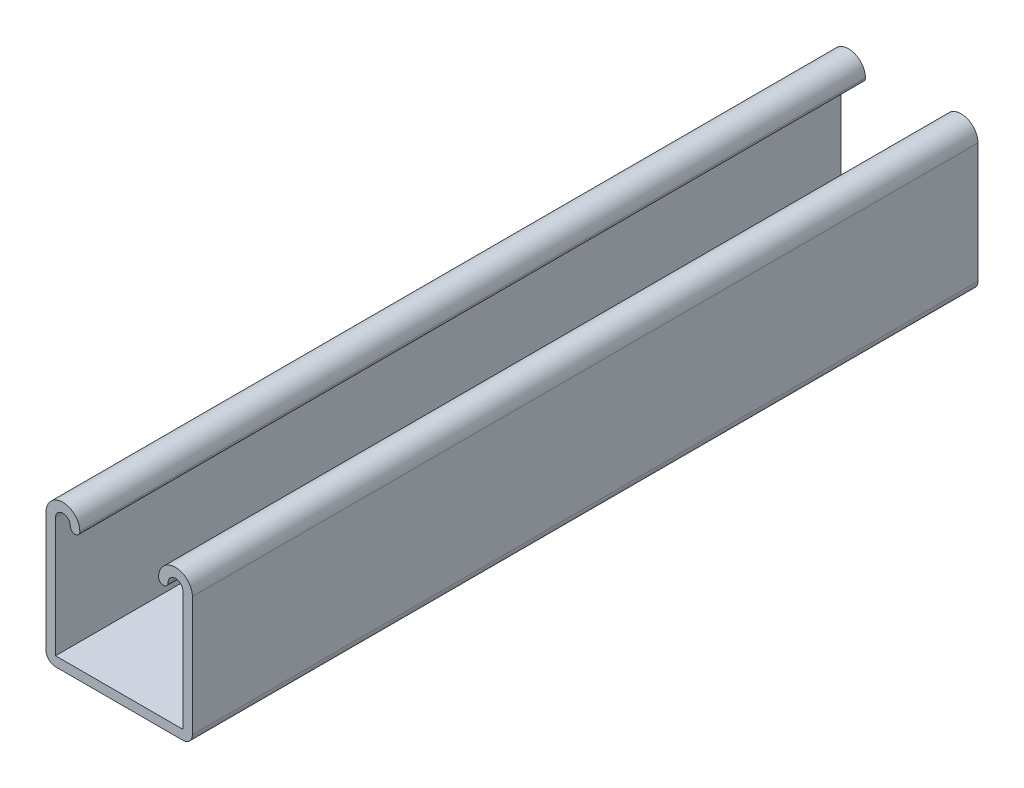
SolidWorks part; units mm, degrees
material "普通碳钢"
ref_plane "前视基准面" through (0, 0, 0) normal (0, 0, 1) x (1, 0, 0)
ref_plane "上视基准面" through (0, 0, 0) normal (0, 1, 0) x (1, 0, 0)
ref_plane "右视基准面" through (0, 0, 0) normal (1, 0, 0) x (0, 0, -1)
sketch "草图1" plane through (0, 0, 0) normal (0, 0, 1) x (1, 0, 0)
  line L0 (0, 0) -> (35.98, 0)
  line L1 (17.99, 2.6924) -> (17.99, -3.3917) construction
  line L2 (35.98, 2.6924) -> (0, 2.6924)
  line L3 (35.98, 19.6088) -> (0, 19.6088) construction
  line L4 (35.98, 2.6924) -> (35.98, 36.5252)
  line L5 (38.6724, 2.6924) -> (38.6724, 36.5252)
  line L6 (-2.6924, 2.6924) -> (-2.6924, 36.5252)
  line L7 (0, 2.6924) -> (0, 36.5252)
  line L8 (17.99, 19.6088) -> (17.99, 2.6924) construction
  arc A0 (35.98, 0) -> (38.6724, 2.6924) centre (35.98, 2.6924) ccw
  arc A1 (35.98, 36.5252) -> (31.8144, 36.5252) centre (33.8972, 36.5252) ccw
  arc A2 (38.6724, 36.5252) -> (29.122, 36.5252) centre (33.8972, 36.5252) ccw
  arc A3 (29.122, 36.5252) -> (31.8144, 36.5252) centre (30.4682, 36.5252) ccw
  arc A4 (6.858, 36.5252) -> (4.1656, 36.5252) centre (5.5118, 36.5252) cw
  arc A5 (-2.6924, 36.5252) -> (6.858, 36.5252) centre (2.0828, 36.5252) cw
  arc A6 (0, 36.5252) -> (4.1656, 36.5252) centre (2.0828, 36.5252) cw
  arc A7 (0, 0) -> (-2.6924, 2.6924) centre (0, 2.6924) cw
  point P25 (17.99, 19.6088)
extrude "凸台-拉伸1" add sketch "草图1" along normal blind 221.996
